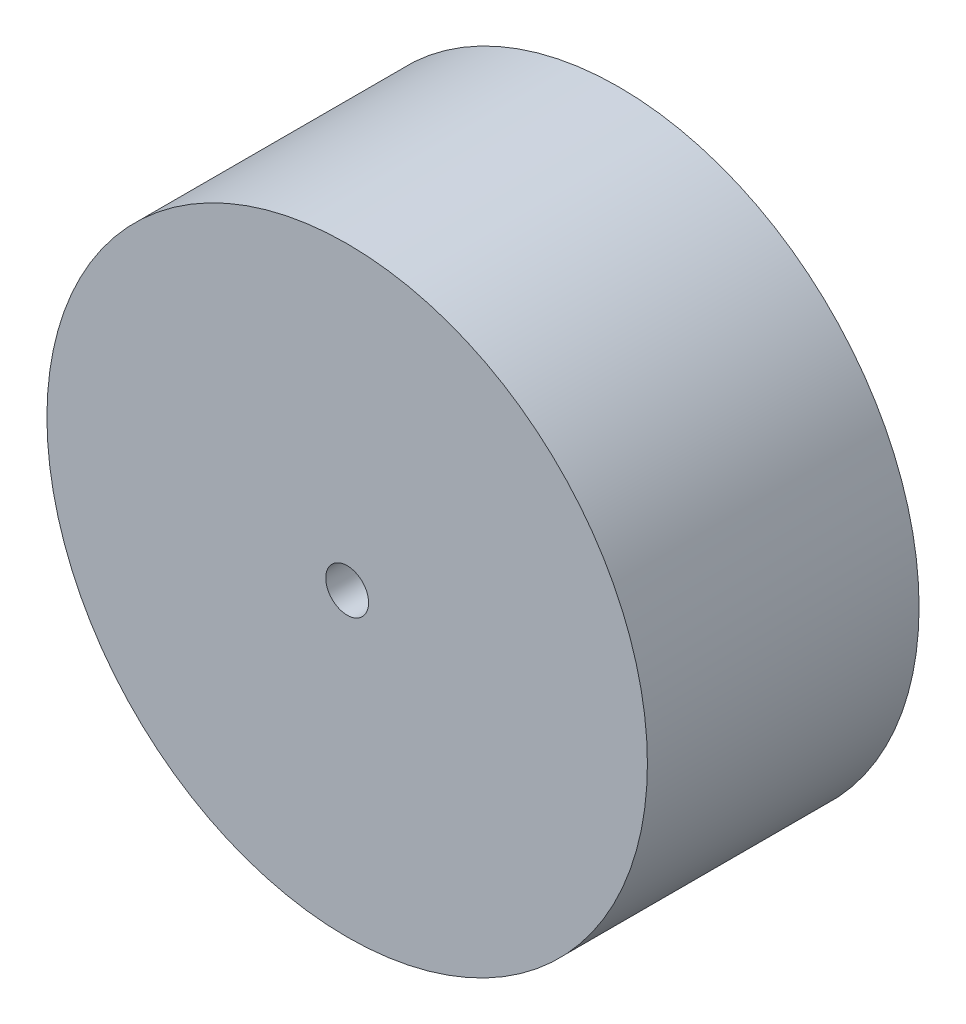
SolidWorks part; units mm, degrees
ref_plane "Front Plane" through (0, 0, 0) normal (0, 0, 1) x (1, 0, 0)
ref_plane "Top Plane" through (0, 0, 0) normal (0, 1, 0) x (1, 0, 0)
ref_plane "Right Plane" through (0, 0, 0) normal (1, 0, 0) x (0, 0, -1)
sketch "Sketch1" plane through (0, 0, 0) normal (0, 0, 1) x (1, 0, 0)
  circle A0 centre (0, 0) radius 21
  dimension "D1" = 42
extrude "Boss-Extrude1" add sketch "Sketch1" along normal blind 19
sketch "Sketch2" plane through (0, 0, 19) normal (0, 0, 1) x (1, 0, 0)
  circle A0 centre (0, 0) radius 1.5
extrude "Cut-Extrude1" cut sketch "Sketch2" against normal through all
